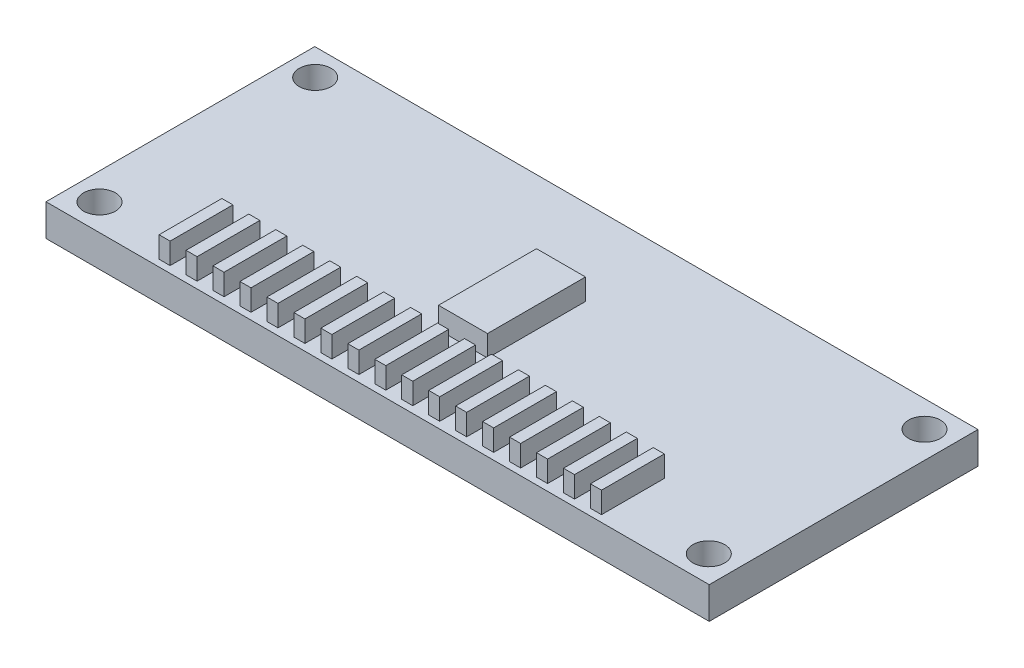
SolidWorks part; units mm, degrees
ref_plane "Front Plane" through (0, 0, 0) normal (0, 0, 1) x (1, 0, 0)
ref_plane "Top Plane" through (0, 0, 0) normal (0, 1, 0) x (1, 0, 0)
ref_plane "Right Plane" through (0, 0, 0) normal (1, 0, 0) x (0, 0, -1)
sketch "Sketch1" plane through (0, 0, 0) normal (0, 1, 0) x (1, 0, 0)
  line L1 (-31.24, -12.66) -> (31.24, -12.66)
  line L2 (-31.24, -12.66) -> (-31.24, 12.66)
  line L3 (-31.24, 12.66) -> (31.24, 12.66)
  line L4 (31.24, -12.66) -> (31.24, 12.66)
  line L5 (-31.24, -12.66) -> (31.24, 12.66) construction
  line L6 (-31.24, 12.66) -> (31.24, -12.66) construction
  circle A0 centre (28.7, 10.16) radius 1.5
  circle A1 centre (28.7, -10.16) radius 1.5
  circle A2 centre (-28.7, 10.16) radius 1.5
  circle A3 centre (-28.7, -10.16) radius 1.5
  point P0 (0, 0)
  dimension "D3" = 3
  dimension "D4" = 57.4
  dimension "D5" = 20.32
  dimension "D6" = 2.5
  dimension "D7" = 2.54
  dimension "D8" = 2.54
  dimension "D1" = 25.32
  dimension "D2" = 62.48
extrude "Boss-Extrude1" add sketch "Sketch1" along normal blind 3
sketch "Sketch2" plane through (0, 3, 0) normal (0, 1, 0) x (1, 0, 0)
  line L0 (-18.6831, -6.1102) -> (-18.6831, -12.0254)
  line L1 (-2.3076, -4.6151) -> (2.3076, -4.6151)
  line L2 (-2.3076, -4.6151) -> (-2.3076, 4.6151)
  line L3 (-2.3076, 4.6151) -> (2.3076, 4.6151)
  line L4 (2.3076, -4.6151) -> (2.3076, 4.6151)
  line L5 (-2.3076, -4.6151) -> (2.3076, 4.6151) construction
  line L6 (-2.3076, 4.6151) -> (2.3076, -4.6151) construction
  line L7 (-21.2231, -6.1102) -> (-20.1831, -6.1102)
  line L8 (-21.2231, -6.1102) -> (-21.2231, -12.0254)
  line L9 (-21.2231, -12.0254) -> (-20.1831, -12.0254)
  line L10 (-20.1831, -6.1102) -> (-20.1831, -12.0254)
  line L11 (-18.6831, -6.1102) -> (-17.6431, -6.1102)
  line L12 (-17.6431, -6.1102) -> (-17.6431, -12.0254)
  line L13 (-18.6831, -12.0254) -> (-17.6431, -12.0254)
  line L14 (-16.1431, -6.1102) -> (-16.1431, -12.0254)
  line L15 (-16.1431, -6.1102) -> (-15.1031, -6.1102)
  line L16 (-15.1031, -6.1102) -> (-15.1031, -12.0254)
  line L17 (-16.1431, -12.0254) -> (-15.1031, -12.0254)
  line L18 (-13.6031, -6.1102) -> (-13.6031, -12.0254)
  line L19 (-13.6031, -6.1102) -> (-12.5631, -6.1102)
  line L20 (-12.5631, -6.1102) -> (-12.5631, -12.0254)
  line L21 (-13.6031, -12.0254) -> (-12.5631, -12.0254)
  line L22 (-11.0631, -6.1102) -> (-11.0631, -12.0254)
  line L23 (-11.0631, -6.1102) -> (-10.0231, -6.1102)
  line L24 (-10.0231, -6.1102) -> (-10.0231, -12.0254)
  line L25 (-11.0631, -12.0254) -> (-10.0231, -12.0254)
  line L26 (-8.5231, -6.1102) -> (-8.5231, -12.0254)
  line L27 (-8.5231, -6.1102) -> (-7.4831, -6.1102)
  line L28 (-7.4831, -6.1102) -> (-7.4831, -12.0254)
  line L29 (-8.5231, -12.0254) -> (-7.4831, -12.0254)
  line L30 (-5.9831, -6.1102) -> (-5.9831, -12.0254)
  line L31 (-5.9831, -6.1102) -> (-4.9431, -6.1102)
  line L32 (-4.9431, -6.1102) -> (-4.9431, -12.0254)
  line L33 (-5.9831, -12.0254) -> (-4.9431, -12.0254)
  line L34 (-3.4431, -6.1102) -> (-3.4431, -12.0254)
  line L35 (-3.4431, -6.1102) -> (-2.4031, -6.1102)
  line L36 (-2.4031, -6.1102) -> (-2.4031, -12.0254)
  line L37 (-3.4431, -12.0254) -> (-2.4031, -12.0254)
  line L38 (-0.9031, -6.1102) -> (-0.9031, -12.0254)
  line L39 (-0.9031, -6.1102) -> (0.1369, -6.1102)
  line L40 (0.1369, -6.1102) -> (0.1369, -12.0254)
  line L41 (-0.9031, -12.0254) -> (0.1369, -12.0254)
  line L42 (1.6369, -6.1102) -> (1.6369, -12.0254)
  line L43 (1.6369, -6.1102) -> (2.6769, -6.1102)
  line L44 (2.6769, -6.1102) -> (2.6769, -12.0254)
  line L45 (1.6369, -12.0254) -> (2.6769, -12.0254)
  line L46 (4.1769, -6.1102) -> (4.1769, -12.0254)
  line L47 (4.1769, -6.1102) -> (5.2169, -6.1102)
  line L48 (5.2169, -6.1102) -> (5.2169, -12.0254)
  line L49 (4.1769, -12.0254) -> (5.2169, -12.0254)
  line L50 (6.7169, -6.1102) -> (6.7169, -12.0254)
  line L51 (6.7169, -6.1102) -> (7.7569, -6.1102)
  line L52 (7.7569, -6.1102) -> (7.7569, -12.0254)
  line L53 (6.7169, -12.0254) -> (7.7569, -12.0254)
  line L54 (9.2569, -6.1102) -> (9.2569, -12.0254)
  line L55 (9.2569, -6.1102) -> (10.2969, -6.1102)
  line L56 (10.2969, -6.1102) -> (10.2969, -12.0254)
  line L57 (9.2569, -12.0254) -> (10.2969, -12.0254)
  line L58 (11.7969, -6.1102) -> (11.7969, -12.0254)
  line L59 (11.7969, -6.1102) -> (12.8369, -6.1102)
  line L60 (12.8369, -6.1102) -> (12.8369, -12.0254)
  line L61 (11.7969, -12.0254) -> (12.8369, -12.0254)
  line L62 (14.3369, -6.1102) -> (14.3369, -12.0254)
  line L63 (14.3369, -6.1102) -> (15.3769, -6.1102)
  line L64 (15.3769, -6.1102) -> (15.3769, -12.0254)
  line L65 (14.3369, -12.0254) -> (15.3769, -12.0254)
  line L66 (16.8769, -6.1102) -> (16.8769, -12.0254)
  line L67 (16.8769, -6.1102) -> (17.9169, -6.1102)
  line L68 (17.9169, -6.1102) -> (17.9169, -12.0254)
  line L69 (16.8769, -12.0254) -> (17.9169, -12.0254)
  line L70 (19.4169, -6.1102) -> (19.4169, -12.0254)
  line L71 (19.4169, -6.1102) -> (20.4569, -6.1102)
  line L72 (20.4569, -6.1102) -> (20.4569, -12.0254)
  line L73 (19.4169, -12.0254) -> (20.4569, -12.0254)
  point P0 (0, 0)
  dimension "D1" = 17
extrude "Boss-Extrude2" add sketch "Sketch2" along normal blind 2
